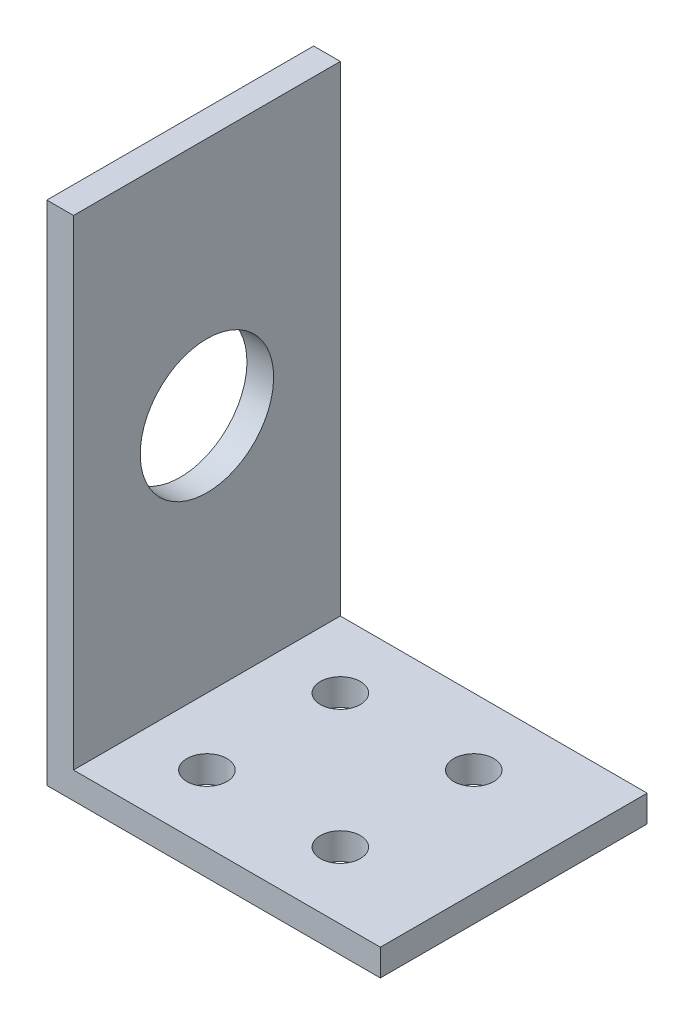
SolidWorks part; units mm, degrees
ref_plane "前视基准面" through (0, 0, 0) normal (0, 0, 1) x (1, 0, 0)
ref_plane "上视基准面" through (0, 0, 0) normal (0, 1, 0) x (1, 0, 0)
ref_plane "右视基准面" through (0, 0, 0) normal (1, 0, 0) x (0, 0, -1)
sketch "草图1" plane through (0, 0, 0) normal (0, 0, 1) x (1, 0, 0)
  line L0 (0, 0) -> (25, 0)
  line L1 (25, 0) -> (25, 2)
  line L2 (25, 2) -> (2, 2)
  line L3 (2, 2) -> (2, 38)
  line L4 (2, 38) -> (0, 38)
  line L5 (0, 38) -> (0, 0)
  dimension "D1" = 2
  dimension "D2" = 2
  dimension "D3" = 25
  dimension "D4" = 38
extrude "凸台-拉伸1" add sketch "草图1" along normal blind 20 contours L5 L0 L1 L2 L3 L4
sketch "草图3" plane through (0, 2, 0) normal (0, 1, 0) x (1, 0, 0)
  line L0 (0, -20) -> (0, 0) construction
  line L1 (25, -20) -> (2, -20) construction
  line L2 (25, 0) -> (2, 0) construction
  circle A0 centre (17, -5) radius 1.5
  circle A1 centre (17, -15) radius 1.5
  circle A2 centre (7, -5) radius 1.5
  circle A3 centre (7, -15) radius 1.5
  dimension "D4" = 3
  dimension "D5" = 3
  dimension "D7" = 3
  dimension "D8" = 3
  dimension "D1" = 17
  dimension "D2" = 5
  dimension "D3" = 5
  dimension "D6" = 10
extrude "切除-拉伸1" cut sketch "草图3" against normal blind 20
sketch "草图4" plane through (2, 0, 0) normal (1, 0, 0) x (0, 0, -1)
  line L0 (0, 38) -> (0, 0) construction
  line L1 (-20, 0) -> (0, 0) construction
  circle A0 centre (-10, 20) radius 5
  dimension "D1" = 10
  dimension "D3" = 10
  dimension "D2" = 20
extrude "切除-拉伸2" cut sketch "草图4" against normal blind 20
